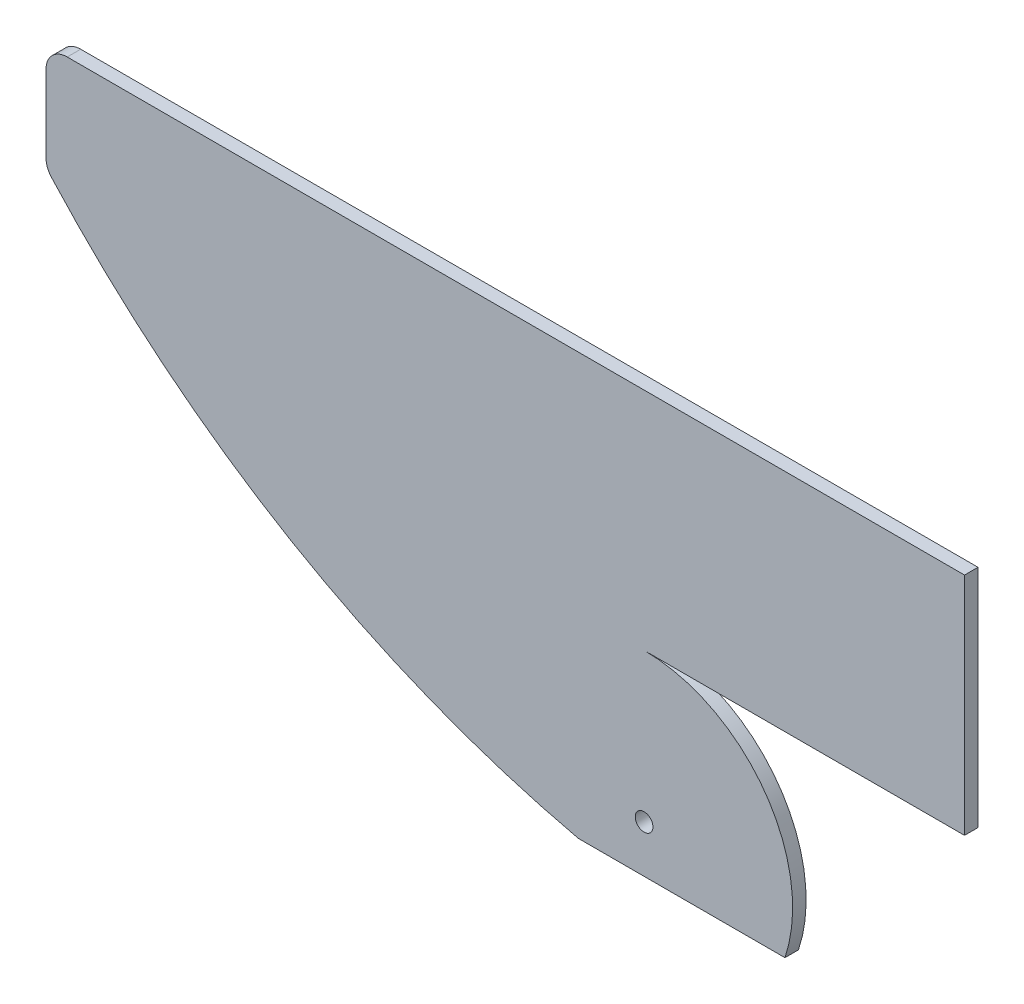
SolidWorks part; units mm, degrees
ref_plane "Alzado" through (0, 0, 0) normal (0, 0, 1) x (1, 0, 0)
ref_plane "Planta" through (0, 0, 0) normal (0, 1, 0) x (1, 0, 0)
ref_plane "Vista lateral" through (0, 0, 0) normal (1, 0, 0) x (0, 0, -1)
sketch "Croquis1" plane through (0, 0, 0) normal (0, 0, 1) x (1, 0, 0)
  line L0 (31, -22.225) -> (333, -22.225)
  line L5 (31, -22.225) -> (-31, -22.225)
  line L6 (31, -22.225) -> (31, 22.225)
  line L11 (31, 22.225) -> (-31, 22.225)
  line L12 (-31, -22.225) -> (-31, 22.225)
  line L13 (31, -22.225) -> (-31, 22.225) construction
  line L14 (31, 22.225) -> (-31, -22.225) construction
  line L15 (-281.8441, 130.0769) -> (-281.8441, 166.245)
  line L16 (151, -22.225) -> (151, 71.3622) construction
  line L17 (583.8441, 130.0769) -> (583.8441, 166.245)
  line L18 (-271.8441, 176.245) -> (573.8441, 176.245)
  arc A2 (-31, -22.225) -> (-279.2561, 123.3642) centre (76.5231, 445.5771) cw
  arc A4 (333, -22.225) -> (581.2561, 123.3642) centre (225.4769, 445.5771) ccw
  arc A5 (583.8441, 130.0769) -> (581.2561, 123.3642) centre (573.8441, 130.0769) cw
  arc A6 (583.8441, 166.245) -> (573.8441, 176.245) centre (573.8441, 166.245) ccw
  arc A7 (-279.2561, 123.3642) -> (-281.8441, 130.0769) centre (-271.8441, 130.0769) cw
  arc A8 (-281.8441, 166.245) -> (-271.8441, 176.245) centre (-271.8441, 166.245) cw
  circle A9 centre (0, 0) radius 4.169
  point P0 (0, 0)
  point P10 (0, 0)
  point P11 (0, 0)
  point P16 (-288.0204, 133.3143)
  point P20 (583.8441, 126.245)
  point P23 (583.8441, 176.245)
  point P26 (-281.8441, 126.245)
  point P29 (-281.8441, 176.245)
  dimension "D1" = 10
  dimension "D2" = 480
  dimension "D5" = 50
  dimension "D3" = 62
  dimension "D4" = 44.45
  dimension "D6" = 120
extrude "Saliente-Extruir1" add sketch "Croquis1" along normal blind 6.35 contours A8 L15 A7 A2 L12 L11 L6 L0 A4 A5 L17 A6 L18 | L12 L5 L6 L11
sketch "Croquis2" plane through (0, 0, 6.35) normal (0, 0, 1) x (1, 0, 0)
  point P0 (0, 0)
sketch "Croquis3" plane through (0, 0, 6.35) normal (0, 0, 1) x (1, 0, 0)
  line L0 (151, 176.245) -> (151, -22.225) construction
  line L1 (-271.8441, 176.245) -> (573.8441, 176.245) construction
  line L2 (-31, -22.225) -> (333, -22.225) construction
  line L3 (0, 70) -> (302, 70)
  line L4 (66.3781, -22.225) -> (235.6219, -22.225)
  arc A0 (66.3781, -22.225) -> (0, 70) centre (0, 0) ccw
  arc A1 (235.6219, -22.225) -> (302, 70) centre (302, 0) cw
  arc A2 (66.3781, -22.225) -> (0, 70) centre (0, 0) ccw
  arc A3 (235.6219, -22.225) -> (302, 70) centre (302, 0) cw
  line M9 (-31, -22.225) -> (333, -22.225)
  dimension "D1" = 140
extrude "Cortar-Extruir1" cut sketch "Croquis3" against normal blind 6.35 contours L0 L3 A0 M9 | L3 L0 L4 A1
sketch "Croquis4" plane through (0, 0, 6.35) normal (0, 0, 1) x (1, 0, 0)
  line L0 (-271.8441, 176.245) -> (573.8441, 176.245) construction
  line L1 (151, 176.245) -> (652.8532, 176.245)
  line L2 (151, 176.245) -> (151, -110.939)
  line L3 (151, -110.939) -> (652.8532, -110.939)
  line L4 (652.8532, 176.245) -> (652.8532, -110.939)
extrude "Cortar-Extruir2" cut sketch "Croquis4" against normal blind 6.35
